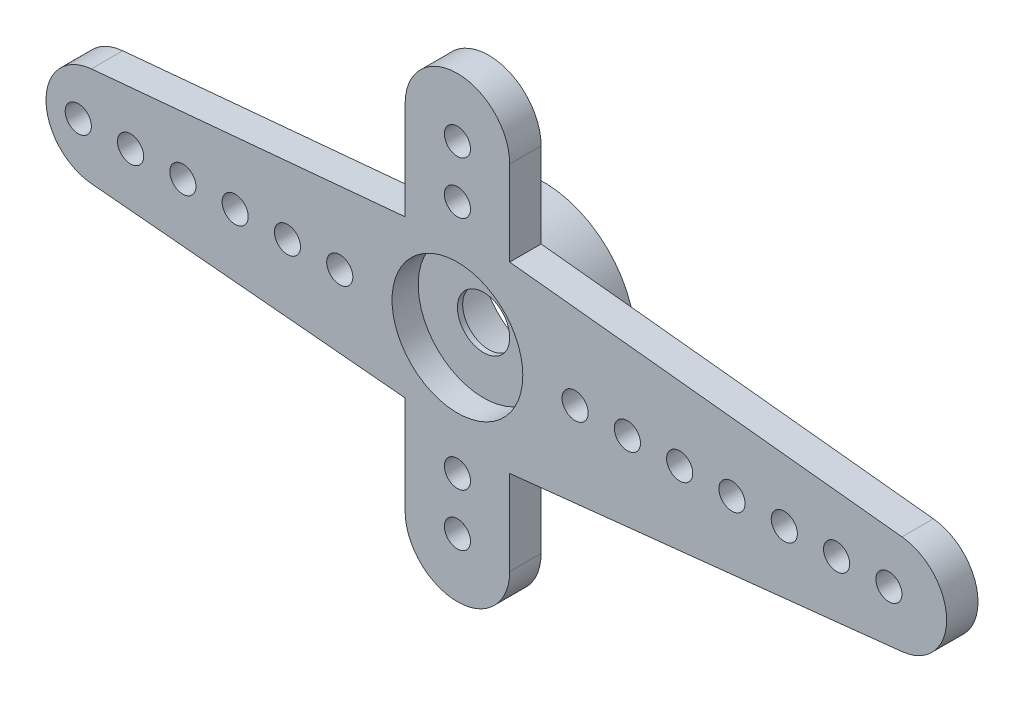
SolidWorks part; units mm, degrees
ref_plane "Front Plane" through (0, 0, 0) normal (0, 0, 1) x (1, 0, 0)
ref_plane "Top Plane" through (0, 0, 0) normal (0, 1, 0) x (1, 0, 0)
ref_plane "Right Plane" through (0, 0, 0) normal (1, 0, 0) x (0, 0, -1)
sketch "Sketch1" plane through (0, 0, 0) normal (0, 0, 1) x (1, 0, 0)
  line L0 (2, 0) -> (17, 0) construction
  line L2 (-2, -6.75) -> (-2, -3)
  line L4 (2, -6.75) -> (2, -3.5)
  line L5 (-2, -6.75) -> (2, 6.75) construction
  line L6 (-2, 6.75) -> (2, -6.75) construction
  line L7 (2, 0) -> (2, 3.5) construction
  line L8 (2, 0) -> (2, -3.5) construction
  line L9 (17, 0) -> (17, 1.9) construction
  line L10 (17, 0) -> (17, -1.9) construction
  line L11 (2, 3.5) -> (17, 1.9)
  line L12 (17, -1.9) -> (2, -3.5)
  line L13 (2, 3.5) -> (2, 6.75)
  line L14 (-2, 0) -> (-2, 3) construction
  line L15 (-2, 0) -> (-2, -3) construction
  line L16 (-2, 0) -> (-14, 0) construction
  line L17 (-14, 0) -> (-14, 1.9) construction
  line L18 (-14, 0) -> (-14, -1.9) construction
  line L19 (-14, 1.9) -> (-2, 3)
  line L20 (-14, -1.9) -> (-2, -3)
  line L21 (-2, 3) -> (-2, 6.75)
  arc A0 (-2, 6.75) -> (2, 6.75) centre (0, 6.75) cw
  arc A1 (2, -6.75) -> (-2, -6.75) centre (0, -6.75) cw
  arc A2 (17, -1.9) -> (17, 1.9) centre (16.7973, 0) ccw
  arc A3 (-14, 1.9) -> (-14, -1.9) centre (-13.8258, 0) ccw
  point P0 (0, 0)
  dimension "D1" = 4
  dimension "D2" = 13.5
  dimension "D3" = 15
  dimension "D4" = 3.5
  dimension "D5" = 3.5
  dimension "D6" = 1.9
  dimension "D7" = 1.9
  dimension "D8" = 3
  dimension "D9" = 3
  dimension "D10" = 12
  dimension "D11" = 1.9
  dimension "D12" = 1.9
extrude "Boss-Extrude1" add sketch "Sketch1" along normal blind 1.2
sketch "Sketch2" plane through (0, 0, 0) normal (0, 0, -1) x (-1, 0, 0)
  line L0 (-2, 3.5) -> (-2, -3.5) construction
  line L1 (2, -3) -> (2, 3) construction
  line L2 (2, 0) -> (-2, 0) construction
  circle A0 centre (0, 0) radius 3.5
  dimension "D1" = 7
extrude "Boss-Extrude2" add sketch "Sketch2" along normal blind 2.1
sketch "Sketch3" plane through (0, 0, 1.2) normal (0, 0, 1) x (1, 0, 0)
  line L0 (-2, 3) -> (-2, -3) construction
  line L1 (2, -3.5) -> (2, 3.5) construction
  line L2 (2, 0) -> (-2, 0) construction
  circle A0 centre (0, 0) radius 2.5
  dimension "D1" = 5
extrude "Cut-Extrude1" cut sketch "Sketch3" against normal blind 1
sketch "Sketch4" plane through (0, 0, 0.2) normal (0, 0, 1) x (1, 0, 0)
  circle A0 centre (0, 0) radius 1
  dimension "D1" = 2
extrude "Cut-Extrude2" cut sketch "Sketch4" against normal through all
sketch "Sketch6" plane through (0, 0, -2.1) normal (0, 0, -1) x (-1, 0, 0)
  circle A0 centre (0, 0) radius 2.45
  dimension "D1" = 4.9
extrude "Cut-Extrude3" cut sketch "Sketch6" against normal blind 2.1
sketch "Sketch7" plane through (0, 0, 1.2) normal (0, 0, 1) x (1, 0, 0)
  line L0 (0, 4.5) -> (0, -4.5) construction
  line L1 (0, -4.5) -> (0, -6.5) construction
  line L2 (0, 0) -> (-0.6381, 0) construction
  line L3 (0, 4.5) -> (0, 6.5) construction
  circle A0 centre (0, -4.5) radius 0.5
  circle A1 centre (0, -6.5) radius 0.5
  circle A2 centre (0, 4.5) radius 0.5
  circle A3 centre (0, 6.5) radius 0.5
  dimension "D3" = 1
  dimension "D4" = 1
  dimension "D5" = 1
  dimension "D6" = 1
  dimension "D1" = 4.5
  dimension "D2" = 2
extrude "Cut-Extrude4" cut sketch "Sketch7" against normal through all
sketch "Sketch8" plane through (0, 0, 1.2) normal (0, 0, 1) x (1, 0, 0)
  line L0 (4.5, 0) -> (-4.5, 0) construction
  line L1 (-4.5, 0) -> (-6.5, 0) construction
  line L2 (-6.5, 0) -> (-8.5, 0) construction
  line L3 (-8.5, 0) -> (-10.5, 0) construction
  line L4 (-10.5, 0) -> (-12.5, 0) construction
  line L5 (-12.5, 0) -> (-14.5, 0) construction
  line L6 (0, 0) -> (0, -0.466) construction
  line L7 (12.5, 0) -> (14.5, 0) construction
  line L8 (10.5, 0) -> (12.5, 0) construction
  line L9 (8.5, 0) -> (10.5, 0) construction
  line L10 (6.5, 0) -> (8.5, 0) construction
  line L11 (4.5, 0) -> (6.5, 0) construction
  line L12 (14.5, 0) -> (16.5, 0) construction
  circle A0 centre (-4.5, 0) radius 0.5
  circle A1 centre (-6.5, 0) radius 0.5
  circle A2 centre (-8.5, 0) radius 0.5
  circle A3 centre (-10.5, 0) radius 0.5
  circle A4 centre (-12.5, 0) radius 0.5
  circle A5 centre (-14.5, 0) radius 0.5
  circle A6 centre (4.5, 0) radius 0.5
  circle A7 centre (6.5, 0) radius 0.5
  circle A8 centre (8.5, 0) radius 0.5
  circle A9 centre (10.5, 0) radius 0.5
  circle A10 centre (12.5, 0) radius 0.5
  circle A11 centre (14.5, 0) radius 0.5
  circle A12 centre (16.5, 0) radius 0.5
  dimension "D7" = 1
  dimension "D8" = 1
  dimension "D9" = 1
  dimension "D10" = 1
  dimension "D11" = 1
  dimension "D12" = 1
  dimension "D14" = 1
  dimension "D1" = 4.5
  dimension "D2" = 2
  dimension "D3" = 2
  dimension "D4" = 2
  dimension "D5" = 2
  dimension "D6" = 2
  dimension "D13" = 2
extrude "Cut-Extrude5" cut sketch "Sketch8" against normal through all
